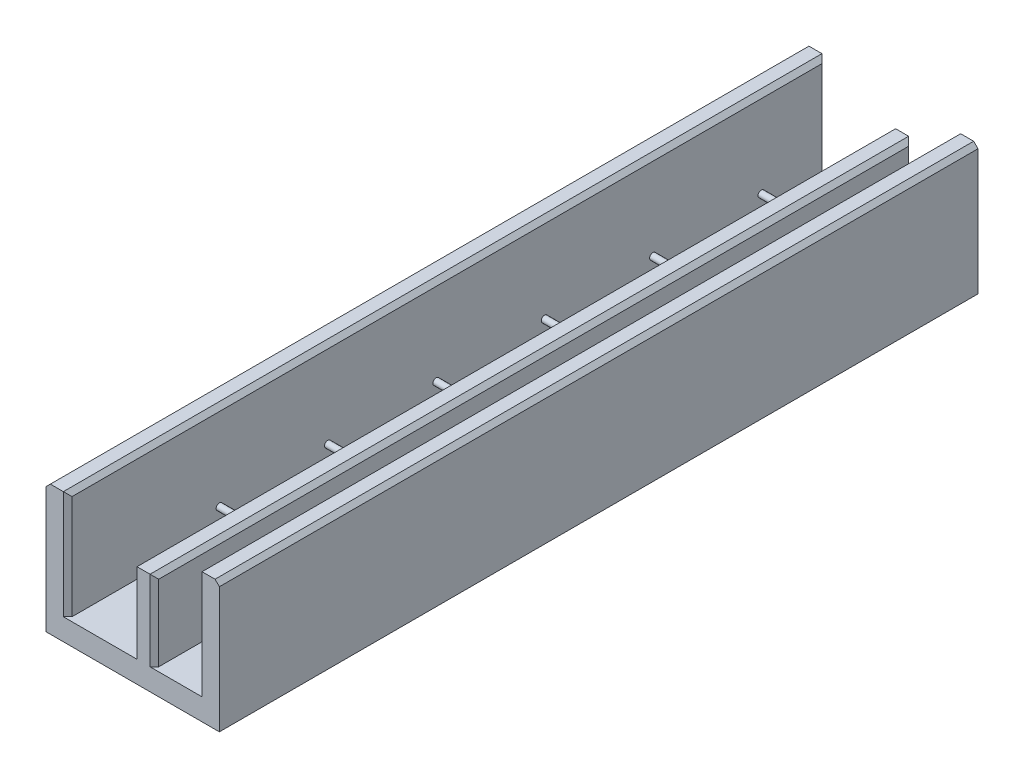
SolidWorks part; units mm, degrees
ref_plane "Alzado" through (0, 0, 0) normal (0, 0, 1) x (1, 0, 0)
ref_plane "Planta" through (0, 0, 0) normal (0, 1, 0) x (1, 0, 0)
ref_plane "Vista lateral" through (0, 0, 0) normal (1, 0, 0) x (0, 0, -1)
sketch "Croquis1" plane through (0, 0, 0) normal (0, 0, 1) x (1, 0, 0)
  line L0 (0, 0) -> (-800, 0)
  line L1 (-800, 0) -> (-800, 600)
  line L2 (-800, 600) -> (-700, 600)
  line L3 (-700, 600) -> (-700, 100)
  line L4 (-700, 100) -> (-400, 100)
  line L5 (-400, 100) -> (-400, 470)
  line L6 (-400, 470) -> (-300, 470)
  line L7 (-300, 470) -> (-300, 100)
  line L8 (-300, 100) -> (-100, 100)
  line L9 (-100, 100) -> (-100, 600)
  line L10 (-100, 600) -> (0, 600)
  line L11 (0, 600) -> (0, 0)
  dimension "D1" = 800
  dimension "D2" = 600
  dimension "D3" = 100
  dimension "D4" = 500
  dimension "D5" = 300
  dimension "D6" = 370
  dimension "D7" = 100
  dimension "D8" = 370
  dimension "D9" = 200
extrude "Saliente-Extruir1" add sketch "Croquis1" along normal blind 3500
chamfer "Chaflán2" distance 20 angle 45 14 edges at (-100, 350, 0) (0, 600, 1750) (-700, 350, 0) (-700, 600, 1750) (-700, 350, 3500) (-100, 350, 3500) (-300, 285, 0) (-300, 285, 3500) (-300, 470, 1750) (-400, 285, 0) (-400, 285, 3500) (-400, 470, 1750) (-800, 600, 1750) (-100, 600, 1750)
sketch "Croquis2" plane through (-800, 0, 0) normal (-1, 0, 0) x (0, 0, 1)
  line L0 (0, 580) -> (0, 0) construction
  circle A0 centre (300, 200) radius 15
  dimension "D3" = 30
  dimension "D1" = 300
extrude "Saliente-Extruir2" add sketch "Croquis2" against normal up to surface (700 mm away) up to face at (-100, 340, 1750)
pattern_linear "MatrizL1" count 6 spacing 500 along (0, 0, 1) of "Saliente-Extruir2"
